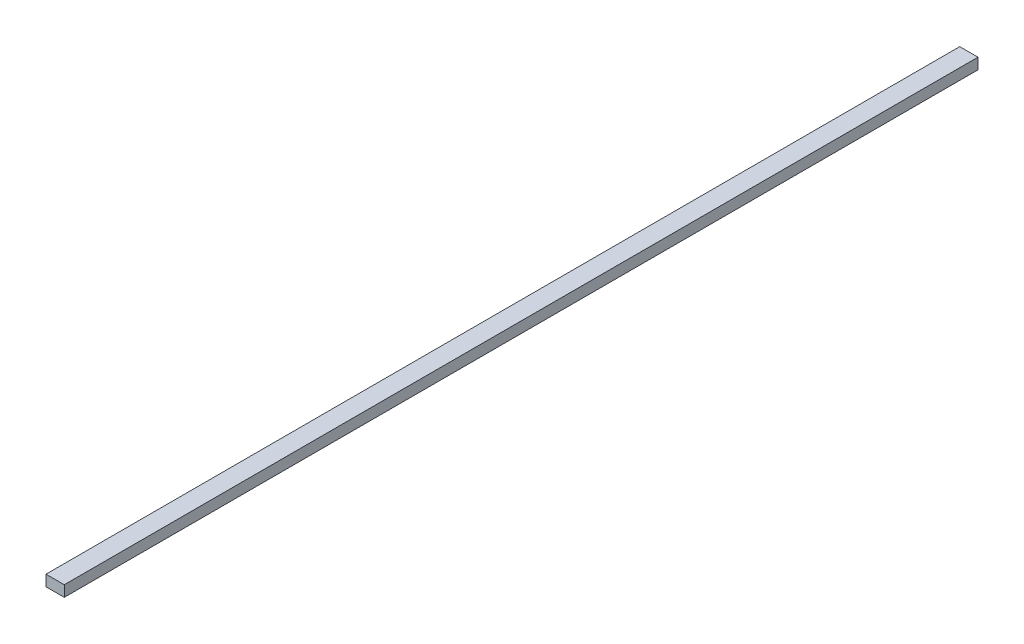
SolidWorks part; units mm, degrees
ref_plane "Спереди" through (0, 0, 0) normal (0, 0, 1) x (1, 0, 0)
ref_plane "Сверху" through (0, 0, 0) normal (0, 1, 0) x (1, 0, 0)
ref_plane "Справа" through (0, 0, 0) normal (1, 0, 0) x (0, 0, -1)
sketch "Эскиз1" plane through (0, 0, 0) normal (0, 0, 1) x (1, 0, 0)
  line L1 (0, 0) -> (50, 0)
  line L2 (0, 0) -> (0, 30)
  line L3 (0, 30) -> (50, 30)
  line L4 (50, 0) -> (50, 30)
  dimension "D1" = 30
  dimension "D2" = 50
extrude "Бобышка-Вытянуть1" add sketch "Эскиз1" against normal blind 2500
